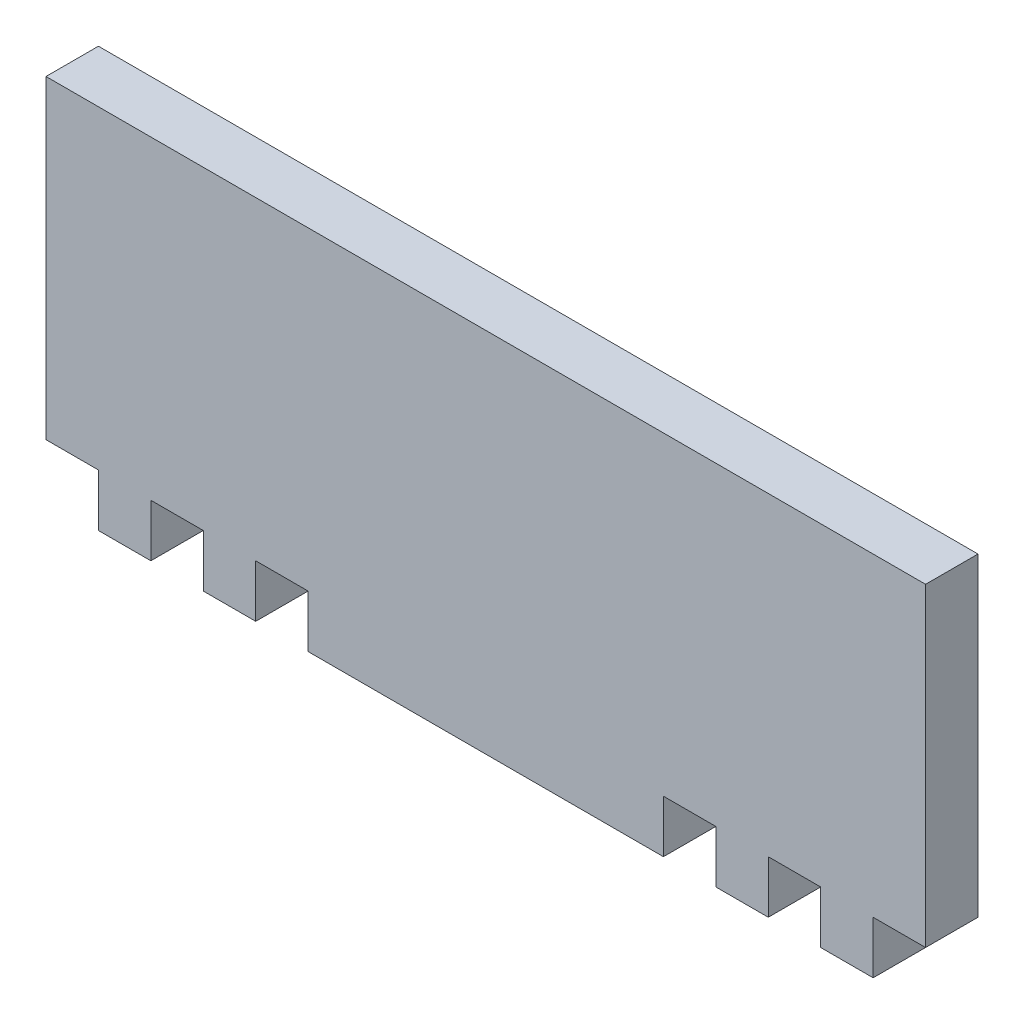
SolidWorks part; units mm, degrees
ref_plane "Plan de face" through (0, 0, 0) normal (0, 0, 1) x (1, 0, 0)
ref_plane "Plan de dessus" through (0, 0, 0) normal (0, 1, 0) x (1, 0, 0)
ref_plane "Plan de droite" through (0, 0, 0) normal (1, 0, 0) x (0, 0, -1)
sketch "Esquisse1" plane through (0, 0, 0) normal (0, 0, 1) x (1, 0, 0)
  line L24 (-95.7657, 49.2291) -> (-90.7657, 49.2291)
  line L25 (-90.7657, 44.2291) -> (-85.7657, 44.2291)
  line L26 (-85.7657, 44.2291) -> (-85.7657, 49.2291)
  line L27 (-85.7657, 49.2291) -> (-80.7657, 49.2291)
  line L28 (-80.7657, 49.2291) -> (-80.7657, 44.2291)
  line L29 (-80.7657, 44.2291) -> (-75.7657, 44.2291)
  line L30 (-75.7657, 44.2291) -> (-75.7657, 49.2291)
  line L31 (-75.7657, 49.2291) -> (-70.7657, 49.2291)
  line L32 (-70.7657, 49.2291) -> (-70.7657, 44.2291)
  line L33 (-70.7657, 44.2291) -> (-36.8847, 44.2291)
  line L34 (-36.8847, 44.2291) -> (-36.8847, 49.2291)
  line L35 (-36.8847, 49.2291) -> (-31.8847, 49.2291)
  line L36 (-31.8847, 49.2291) -> (-31.8847, 44.2291)
  line L37 (-31.8847, 44.2291) -> (-26.8847, 44.2291)
  line L38 (-26.8847, 44.2291) -> (-26.8847, 49.2291)
  line L39 (-26.8847, 49.2291) -> (-21.8847, 49.2291)
  line L40 (-21.8847, 49.2291) -> (-21.8847, 44.2291)
  line L41 (-21.8847, 44.2291) -> (-16.8847, 44.2291)
  line L42 (-16.8847, 44.2291) -> (-16.8847, 49.2291)
  line L43 (-16.8847, 49.2291) -> (-11.8847, 49.2291)
  line L44 (-11.8847, 49.2291) -> (-11.8847, 79.2291)
  line L45 (-11.8847, 79.2291) -> (-95.7657, 79.2291)
  line L46 (-95.7657, 79.2291) -> (-95.7657, 49.2291)
  line L47 (-90.7657, 49.2291) -> (-90.7657, 44.2291)
  point P51 (-31.8847, 46.7291)
  dimension "D2" = 5
  dimension "D3" = 5
  dimension "D4" = 30
extrude "Boss.-Extru.1" add sketch "Esquisse1" along normal blind 5
